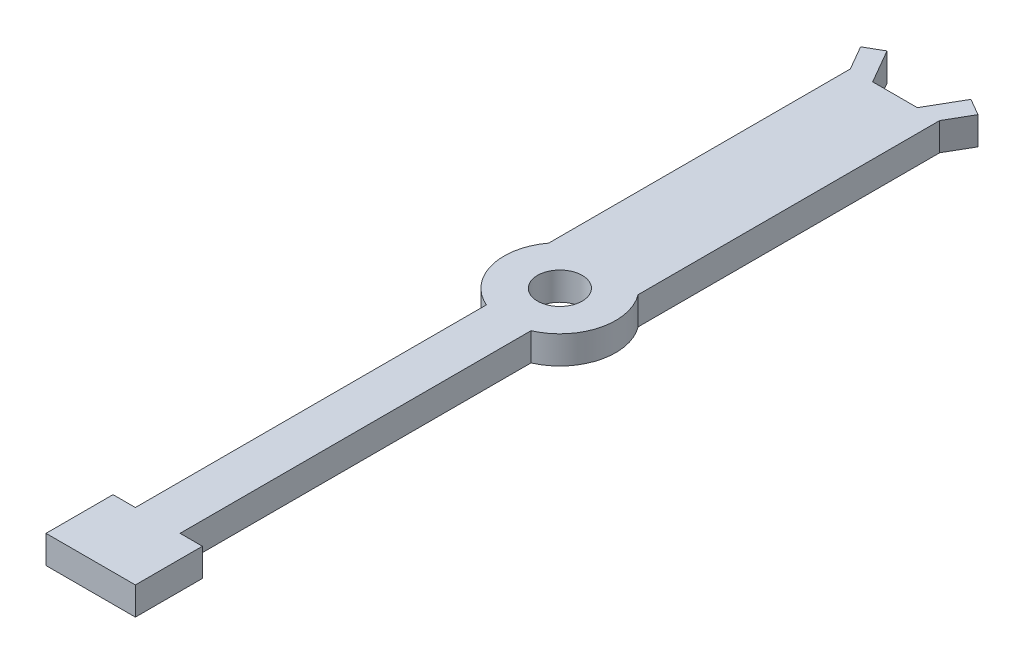
SolidWorks part; units mm, degrees
ref_plane "Front Plane" through (0, 0, 0) normal (0, 0, 1) x (1, 0, 0)
ref_plane "Top Plane" through (0, 0, 0) normal (0, 1, 0) x (1, 0, 0)
ref_plane "Right Plane" through (0, 0, 0) normal (1, 0, 0) x (0, 0, -1)
sketch "Sketch1" plane through (0, 0, 0) normal (0, 1, 0) x (1, 0, 0)
  line L0 (0, 21.9808) -> (0, 49.7111) construction
  line L1 (-4, -30) -> (4, -30)
  line L2 (-4, -30) -> (-4, 30)
  line L3 (-4, 30) -> (4, 30)
  line L4 (4, -30) -> (4, 30)
  line L5 (-4, -30) -> (4, 30) construction
  line L6 (-4, 30) -> (4, -30) construction
  line L7 (-4, 30) -> (-5.2551, 32.1738)
  line L8 (-5.2551, 32.1738) -> (-3.7551, 33.0398)
  line L9 (-3.7551, 33.0398) -> (-2, 30)
  line L10 (5.2551, 32.1738) -> (3.7551, 33.0398)
  line L11 (3.7551, 33.0398) -> (2, 30)
  line L12 (4, 30) -> (5.2551, 32.1738)
  line L14 (-4, -30) -> (4, -30)
  line L15 (-4, -30) -> (-4, -42)
  line L16 (-4, -42) -> (4, -42)
  line L17 (4, -30) -> (4, -42)
  line L18 (-4, -30) -> (-2, -30)
  line L19 (-4, -30) -> (-4, -2)
  line L20 (-4, -2) -> (-2, -2)
  line L21 (-2, -30) -> (-2, -2)
  line L22 (4, -30) -> (2, -30)
  line L23 (4, -30) -> (4, -2)
  line L24 (4, -2) -> (2, -2)
  line L25 (2, -30) -> (2, -2)
  line L26 (-2, -30) -> (-4, -30)
  line L27 (-2, -30) -> (-2, -36)
  line L28 (-2, -36) -> (-4, -36)
  line L29 (-4, -30) -> (-4, -36)
  line L30 (2, -30) -> (4, -30)
  line L31 (2, -30) -> (2, -36)
  line L32 (2, -36) -> (4, -36)
  line L33 (4, -30) -> (4, -36)
  circle A0 centre (0, 0) radius 2
  circle A1 centre (0, 0) radius 5
  dimension "D2" = 3
  dimension "D3" = 4
  dimension "D1" = 60
  dimension "D4" = 8
  dimension "D5" = 4
  dimension "D6" = 12
extrude "Boss-Extrude1" add sketch "Sketch1" along normal blind 2.5 contours A1 L2 L1 L4 | L2 A1 | L4 A1 L2 A0 | L2 A1 L4 A0 | L4 A1 | A1 L4 L3 L2 | L9 L8 L7 L3 | L3 L12 L10 L11 | L17 L1 L15 L16 | L25 A1 L23 L24
